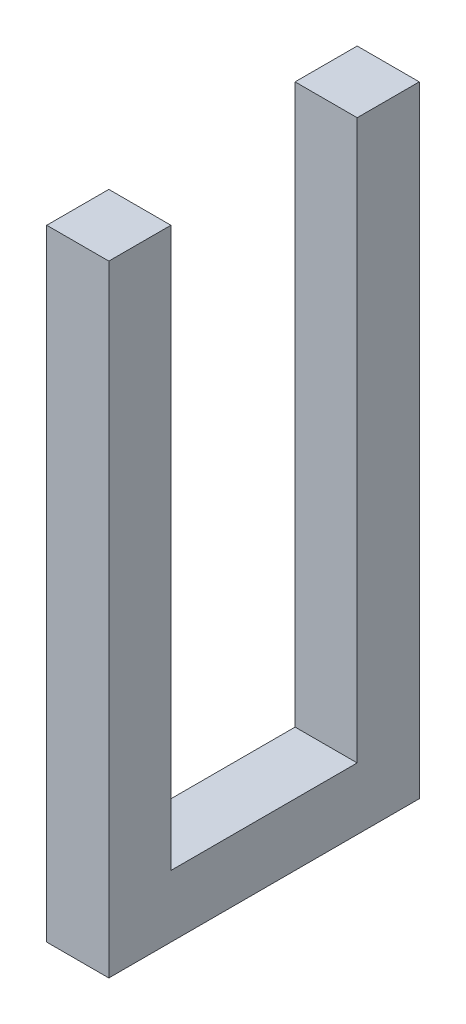
SolidWorks part; units mm, degrees
ref_plane "Alzado" through (0, 0, 0) normal (0, 0, 1) x (1, 0, 0)
ref_plane "Planta" through (0, 0, 0) normal (0, 1, 0) x (1, 0, 0)
ref_plane "Vista lateral" through (0, 0, 0) normal (1, 0, 0) x (0, 0, -1)
sketch "Croquis1" plane through (0, 0, 0) normal (1, 0, 0) x (0, 0, -1)
  line L0 (0, 0) -> (0, 100)
  line L1 (10, 100) -> (10, 10)
  line L2 (10, 10) -> (40, 10)
  line L3 (40, 10) -> (40, 100)
  line L4 (40, 100) -> (50, 100)
  line L5 (50, 100) -> (50, 0)
  line L6 (50, 0) -> (0, 0)
  line L7 (0, 100) -> (10, 100)
  dimension "D1" = 10
  dimension "D2" = 10
  dimension "D3" = 10
  dimension "D4" = 50
  dimension "D6" = 100
extrude "Saliente-Extruir1" add sketch "Croquis1" along normal blind 10
